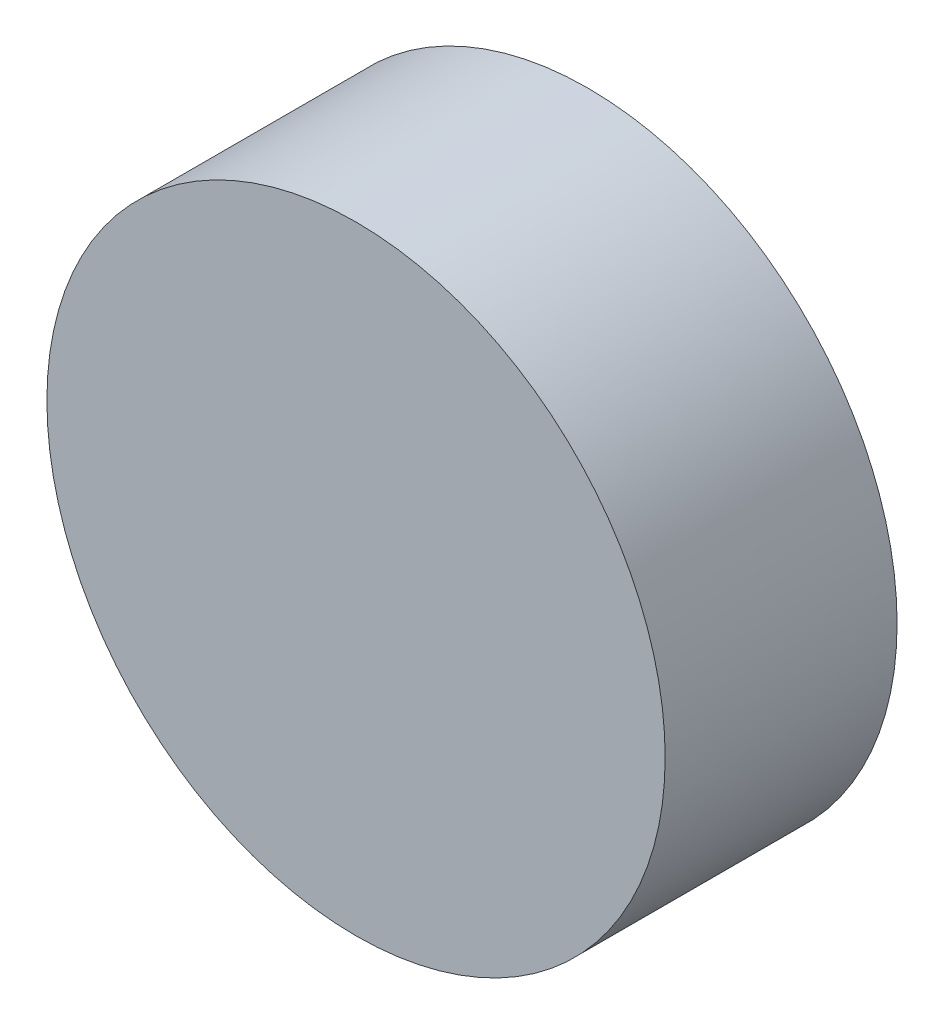
SolidWorks part; units mm, degrees
ref_plane "Front" through (0, 0, 0) normal (0, 0, 1) x (1, 0, 0)
ref_plane "Top" through (0, 0, 0) normal (0, 1, 0) x (1, 0, 0)
ref_plane "Right" through (0, 0, 0) normal (1, 0, 0) x (0, 0, -1)
sketch "Sketch2" plane through (0, 0, 0) normal (0, 1, 0) x (1, 0, 0)
  line L0 (0, 0) -> (0, 3.0569)
  line L7 (4, 0) -> (4, 2.8287)
  line L8 (4, 0) -> (0, 0)
  arc A2 (4, 2.8287) -> (0, 3.0569) centre (0, -32.1183) ccw
  dimension "D1" = 35.1752
  dimension "D2" = 4
  dimension "D3" = 2.8287
revolve "Revolve1" add sketch "Sketch2" angle 360 about L0
sketch "Sketch3" plane through (0, 0, 0) normal (0, 0, 1) x (1, 0, 0)
  circle A0 centre (0, 0) radius 4
  circle A1 centre (0, 0) radius 3.8
  circle A2 centre (0, 0) radius 4 construction
  dimension "D2" = 7.6
  dimension "D1" = 0.2
extrude "Cut-Extrude1" cut sketch "Sketch3" against normal through all
